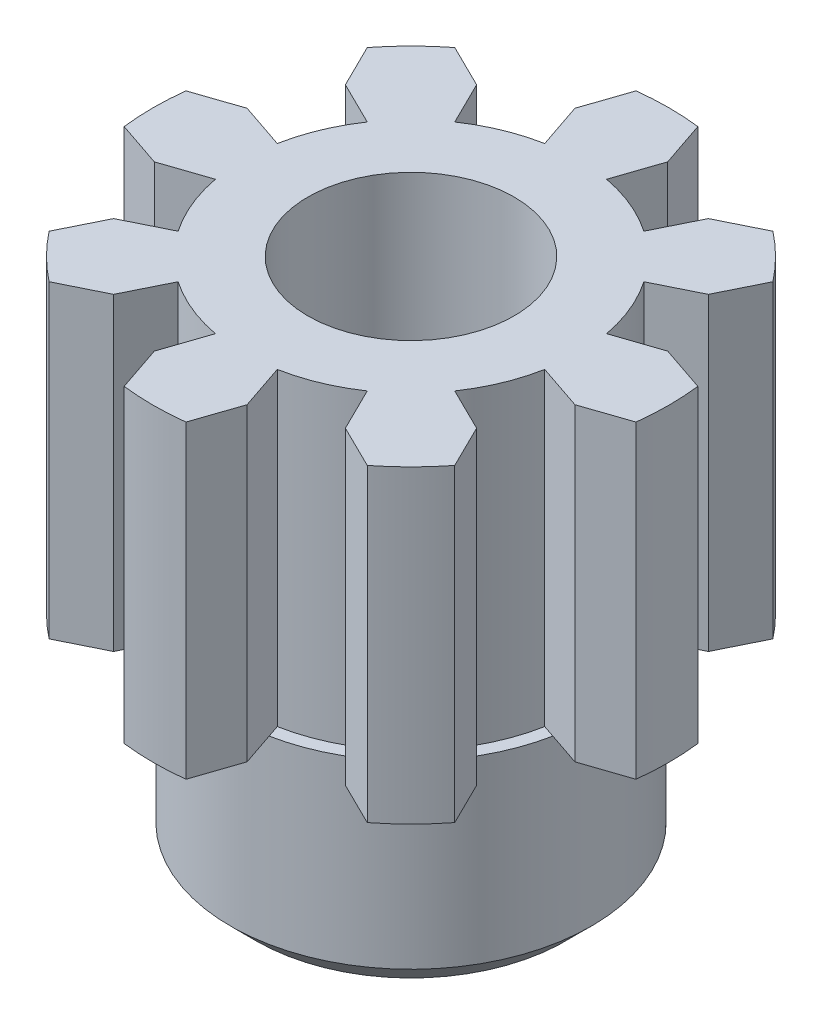
SolidWorks part; units mm, degrees
material "ABS"
ref_plane "Plano frontal" through (0, 0, 0) normal (0, 0, 1) x (1, 0, 0)
ref_plane "Plano superior" through (0, 0, 0) normal (0, 1, 0) x (1, 0, 0)
ref_plane "Plano direito" through (0, 0, 0) normal (1, 0, 0) x (0, 0, -1)
sketch "Esboço1" plane through (0, 0, 0) normal (0, 0, 1) x (1, 0, 0)
  line L0 (2.5, 3) -> (0, 3)
  line L1 (0, 3) -> (0, 0)
  line L2 (0, 0) -> (2.5, 0)
  line L3 (2.5, 0) -> (2.5, 3)
  line L4 (0, 3) -> (0, 0) construction
revolve "Revolução1" add sketch "Esboço1" angle 360 about L4
sketch "Esboço2" plane through (0, 0, 0) normal (0, -1, 0) x (1, 0, 0)
  line L0 (-0.3, -2.4819) -> (-0.6277, -1.5154)
  line L1 (-0.6277, -1.5154) -> (-1.5429, -1.9671)
  arc A0 (-1.5429, -1.9671) -> (-0.3, -2.4819) centre (0, 0) ccw
extrude "Corte-extrusão1" cut sketch "Esboço2" against normal through all
sketch "Esboço3" plane through (0, 0, 0) normal (0, -1, 0) x (1, 0, 0)
  line L0 (-0.9172, -1.3414) -> (-1.1239, -1.7603)
  line L1 (-1.1239, -1.7603) -> (-0.6277, -1.5154)
  line L2 (-0.6277, -1.5154) -> (-0.45, -2.0395)
  line L3 (-0.45, -2.0395) -> (-0.3, -1.5971)
  arc A0 (-0.3, -1.5971) -> (-0.9172, -1.3414) centre (0, 0) cw
extrude "Corte-extrusão2" cut sketch "Esboço3" against normal through all
sketch "Esboço4" plane through (0, 0, 0) normal (0, -1, 0) x (1, 0, 0)
  line L0 (-1.9671, -1.5429) -> (-1.5154, -0.6277)
  line L1 (-1.5154, -0.6277) -> (-2.4819, -0.3)
  arc A0 (-2.4819, -0.3) -> (-1.9671, -1.5429) centre (0, 0) ccw
extrude "Corte-extrusão3" cut sketch "Esboço4" against normal through all
sketch "Esboço5" plane through (0, 0, 0) normal (0, -1, 0) x (1, 0, 0)
  line L0 (-1.5971, -0.3) -> (-2.0395, -0.45)
  line L1 (-2.0395, -0.45) -> (-1.5154, -0.6277)
  line L2 (-1.5154, -0.6277) -> (-1.7603, -1.1239)
  line L3 (-1.7603, -1.1239) -> (-1.3414, -0.9172)
  arc A0 (-1.3414, -0.9172) -> (-1.5971, -0.3) centre (0, 0) cw
extrude "Corte-extrusão4" cut sketch "Esboço5" against normal through all
sketch "Esboço6" plane through (0, 0, 0) normal (0, -1, 0) x (1, 0, 0)
  line L0 (-2.4819, 0.3) -> (-1.5154, 0.6277)
  line L1 (-1.5154, 0.6277) -> (-1.9671, 1.5429)
  arc A0 (-1.9671, 1.5429) -> (-2.4819, 0.3) centre (0, 0) ccw
extrude "Corte-extrusão5" cut sketch "Esboço6" against normal through all
sketch "Esboço7" plane through (0, 0, 0) normal (0, -1, 0) x (1, 0, 0)
  line L0 (-1.3414, 0.9172) -> (-1.7603, 1.1239)
  line L1 (-1.7603, 1.1239) -> (-1.5154, 0.6277)
  line L2 (-1.5154, 0.6277) -> (-2.0395, 0.45)
  line L3 (-2.0395, 0.45) -> (-1.5971, 0.3)
  arc A0 (-1.5971, 0.3) -> (-1.3414, 0.9172) centre (0, 0) cw
extrude "Corte-extrusão6" cut sketch "Esboço7" against normal through all
sketch "Esboço8" plane through (0, 0, 0) normal (0, -1, 0) x (1, 0, 0)
  line L0 (-1.5429, 1.9671) -> (-0.6277, 1.5154)
  line L1 (-0.6277, 1.5154) -> (-0.3, 2.4819)
  arc A0 (-0.3, 2.4819) -> (-1.5429, 1.9671) centre (0, 0) ccw
extrude "Corte-extrusão7" cut sketch "Esboço8" against normal through all
sketch "Esboço9" plane through (0, 0, 0) normal (0, -1, 0) x (1, 0, 0)
  line L0 (-0.3, 1.5971) -> (-0.45, 2.0395)
  line L1 (-0.45, 2.0395) -> (-0.6277, 1.5154)
  line L2 (-0.6277, 1.5154) -> (-1.1239, 1.7603)
  line L3 (-1.1239, 1.7603) -> (-0.9172, 1.3414)
  arc A0 (-0.9172, 1.3414) -> (-0.3, 1.5971) centre (0, 0) cw
extrude "Corte-extrusão8" cut sketch "Esboço9" against normal through all
sketch "Esboço10" plane through (0, 0, 0) normal (0, -1, 0) x (1, 0, 0)
  line L0 (0.3, 2.4819) -> (0.6277, 1.5154)
  line L1 (0.6277, 1.5154) -> (1.5429, 1.9671)
  arc A0 (1.5429, 1.9671) -> (0.3, 2.4819) centre (0, 0) ccw
extrude "Corte-extrusão9" cut sketch "Esboço10" against normal through all
sketch "Esboço11" plane through (0, 0, 0) normal (0, -1, 0) x (1, 0, 0)
  line L0 (0.9172, 1.3414) -> (1.1239, 1.7603)
  line L1 (1.1239, 1.7603) -> (0.6277, 1.5154)
  line L2 (0.6277, 1.5154) -> (0.45, 2.0395)
  line L3 (0.45, 2.0395) -> (0.3, 1.5971)
  arc A0 (0.3, 1.5971) -> (0.9172, 1.3414) centre (0, 0) cw
extrude "Corte-extrusão10" cut sketch "Esboço11" against normal through all
sketch "Esboço12" plane through (0, 0, 0) normal (0, -1, 0) x (1, 0, 0)
  line L0 (1.9671, 1.5429) -> (1.5154, 0.6277)
  line L1 (1.5154, 0.6277) -> (2.4819, 0.3)
  arc A0 (2.4819, 0.3) -> (1.9671, 1.5429) centre (0, 0) ccw
extrude "Corte-extrusão11" cut sketch "Esboço12" against normal through all
sketch "Esboço13" plane through (0, 0, 0) normal (0, -1, 0) x (1, 0, 0)
  line L0 (1.5971, 0.3) -> (2.0395, 0.45)
  line L1 (2.0395, 0.45) -> (1.5154, 0.6277)
  line L2 (1.5154, 0.6277) -> (1.7603, 1.1239)
  line L3 (1.7603, 1.1239) -> (1.3414, 0.9172)
  arc A0 (1.3414, 0.9172) -> (1.5971, 0.3) centre (0, 0) cw
extrude "Corte-extrusão12" cut sketch "Esboço13" against normal through all
sketch "Esboço14" plane through (0, 0, 0) normal (0, -1, 0) x (1, 0, 0)
  line L0 (2.4819, -0.3) -> (1.5154, -0.6277)
  line L1 (1.5154, -0.6277) -> (1.9671, -1.5429)
  arc A0 (1.9671, -1.5429) -> (2.4819, -0.3) centre (0, 0) ccw
extrude "Corte-extrusão13" cut sketch "Esboço14" against normal through all
sketch "Esboço15" plane through (0, 0, 0) normal (0, -1, 0) x (1, 0, 0)
  line L0 (1.3414, -0.9172) -> (1.7603, -1.1239)
  line L1 (1.7603, -1.1239) -> (1.5154, -0.6277)
  line L2 (1.5154, -0.6277) -> (2.0395, -0.45)
  line L3 (2.0395, -0.45) -> (1.5971, -0.3)
  arc A0 (1.5971, -0.3) -> (1.3414, -0.9172) centre (0, 0) cw
extrude "Corte-extrusão14" cut sketch "Esboço15" against normal through all
sketch "Esboço16" plane through (0, 0, 0) normal (0, -1, 0) x (1, 0, 0)
  line L0 (1.5429, -1.9671) -> (0.6277, -1.5154)
  line L1 (0.6277, -1.5154) -> (0.3, -2.4819)
  arc A0 (0.3, -2.4819) -> (1.5429, -1.9671) centre (0, 0) ccw
extrude "Corte-extrusão15" cut sketch "Esboço16" against normal through all
sketch "Esboço17" plane through (0, 0, 0) normal (0, -1, 0) x (1, 0, 0)
  line L0 (0.6277, -1.5154) -> (1.1239, -1.7603)
  line L1 (1.1239, -1.7603) -> (0.9172, -1.3414)
  line L2 (0.3, -1.5971) -> (0.45, -2.0395)
  line L3 (0.45, -2.0395) -> (0.6277, -1.5154)
  arc A0 (0.9172, -1.3414) -> (0.3, -1.5971) centre (0, 0) cw
extrude "Corte-extrusão16" cut sketch "Esboço17" against normal through all
sketch "Esboço18" plane through (0, 0, 0) normal (0, -1, 0) x (1, 0, 0)
  circle A0 centre (0, 0) radius 1.75
extrude "Ressalto-extrusão1" add sketch "Esboço18" along normal blind 2
hole_wizard "Furo de diâmetro Ø2.0 (2)1" positions "Esboço20" profile "Esboço19" hole size "Ø2.0" standard "Ansi Metric"
sketch "Esboço20" plane through (0, 3, 0) normal (0, 1, 0) x (1, 0, 0)
  point P0 (0, 0)
sketch "Esboço19" plane through (0, 3, 0) normal (1, 0, 0) x (0, 0, 1)
  line L0 (0, 0) -> (0, 5)
  line L1 (0, 5) -> (1, 5)
  line L2 (1, 5) -> (1, 0)
  line L5 (1, 0) -> (0, 0)
  line L11 (0, -6.35) -> (0, 107.95) construction
  dimension "Thru Hole Dia." = 2
  dimension "Thru Hole Depth" = 5
chamfer "Chanfro1" distance 0.25 angle 45 1 edges at (0, -2, -1.75)
